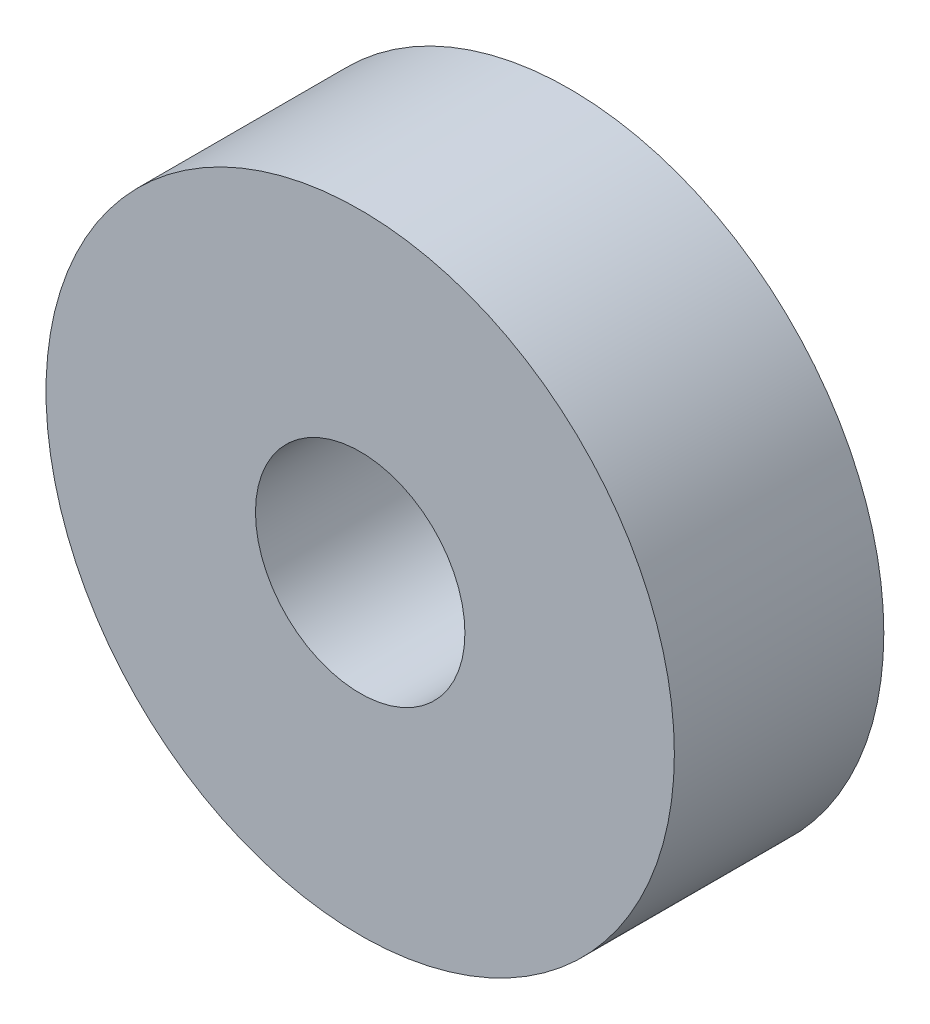
SolidWorks part; units mm, degrees
ref_plane "Front Plane" through (0, 0, 0) normal (0, 0, 1) x (1, 0, 0)
ref_plane "Top Plane" through (0, 0, 0) normal (0, 1, 0) x (1, 0, 0)
ref_plane "Right Plane" through (0, 0, 0) normal (1, 0, 0) x (0, 0, -1)
sketch "Sketch1" plane through (0, 0, 0) normal (0, 0, 1) x (1, 0, 0)
  circle A0 centre (0, 0) radius 0.5
  circle A1 centre (0, 0) radius 1.5
  dimension "D1" = 1
  dimension "D2" = 1
extrude "Boss-Extrude1" add sketch "Sketch1" along normal blind 1
